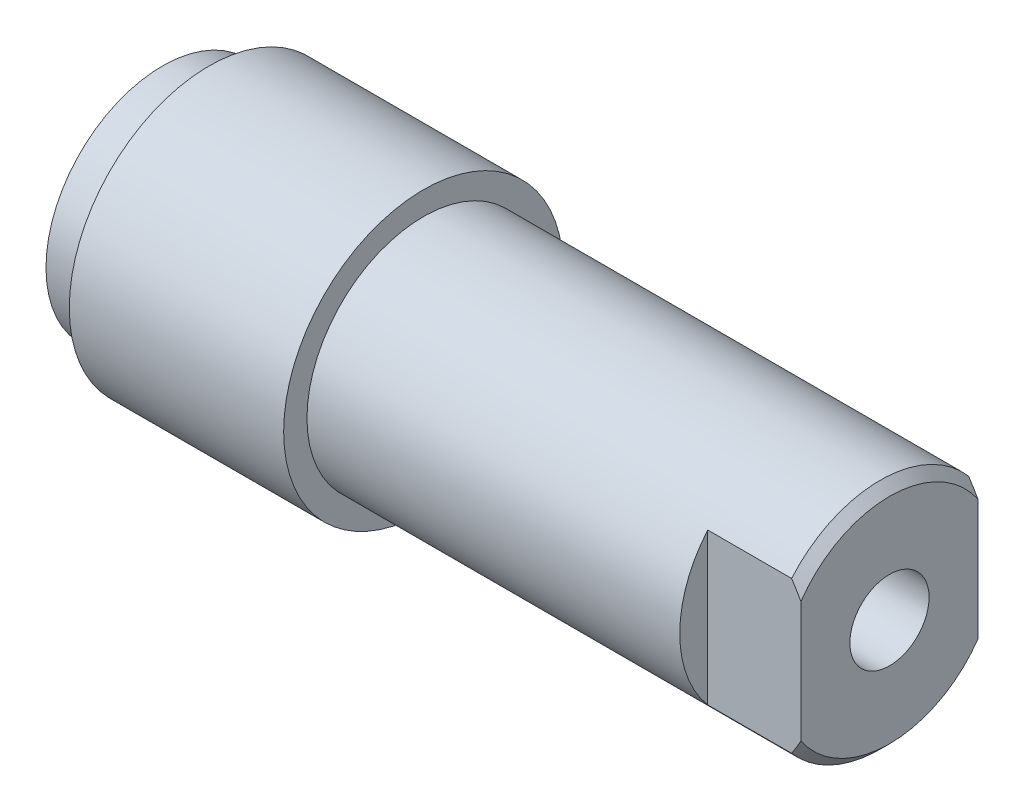
SolidWorks part; units mm, degrees
ref_plane "正面" through (0, 0, 0) normal (0, 0, 1) x (1, 0, 0)
ref_plane "平面" through (0, 0, 0) normal (0, 1, 0) x (1, 0, 0)
ref_plane "右側面" through (0, 0, 0) normal (1, 0, 0) x (0, 0, -1)
sketch "ｽｹｯﾁ1" plane through (0, 0, 0) normal (0, 0, 1) x (1, 0, 0)
  line L0 (-78, 0) -> (-78, 12.5)
  line L1 (-78, 12.5) -> (-73, 12.5)
  line L2 (-73, 12.5) -> (-73, 15)
  line L3 (-73, 15) -> (-50, 15)
  line L4 (-50, 15) -> (-50, 12.5)
  line L5 (-50, 12.5) -> (-1, 12.5)
  line L6 (-1, 12.5) -> (0, 11.5)
  line L7 (0, 11.5) -> (0, 0)
  line L8 (0, 0) -> (-78, 0)
  line L9 (-78, 0) -> (0, 0) construction
revolve "回転1" add sketch "ｽｹｯﾁ1" angle 360 about L9
sketch "ｽｹｯﾁ2" plane through (0, 0, 0) normal (1, 0, 0) x (0, 0, -1)
  line L0 (9.5, -14) -> (14, -14)
  line L1 (14, -14) -> (14, 14)
  line L2 (14, 14) -> (9.5, 14)
  line L3 (9.5, 14) -> (9.5, -14)
  line L4 (-14, -14) -> (-9.5, -14)
  line L5 (-9.5, -14) -> (-9.5, 14)
  line L6 (-9.5, 14) -> (-14, 14)
  line L7 (-14, 14) -> (-14, -14)
extrude "ｶｯﾄ - 押し出し1" cut sketch "ｽｹｯﾁ2" against normal blind 10
sketch "ｽｹｯﾁ3" plane through (0, 0, 0) normal (1, 0, 0) x (0, 0, -1)
  circle A0 centre (0, 0) radius 4.25
extrude "ｶｯﾄ - 押し出し2" cut sketch "ｽｹｯﾁ3" against normal blind 20
